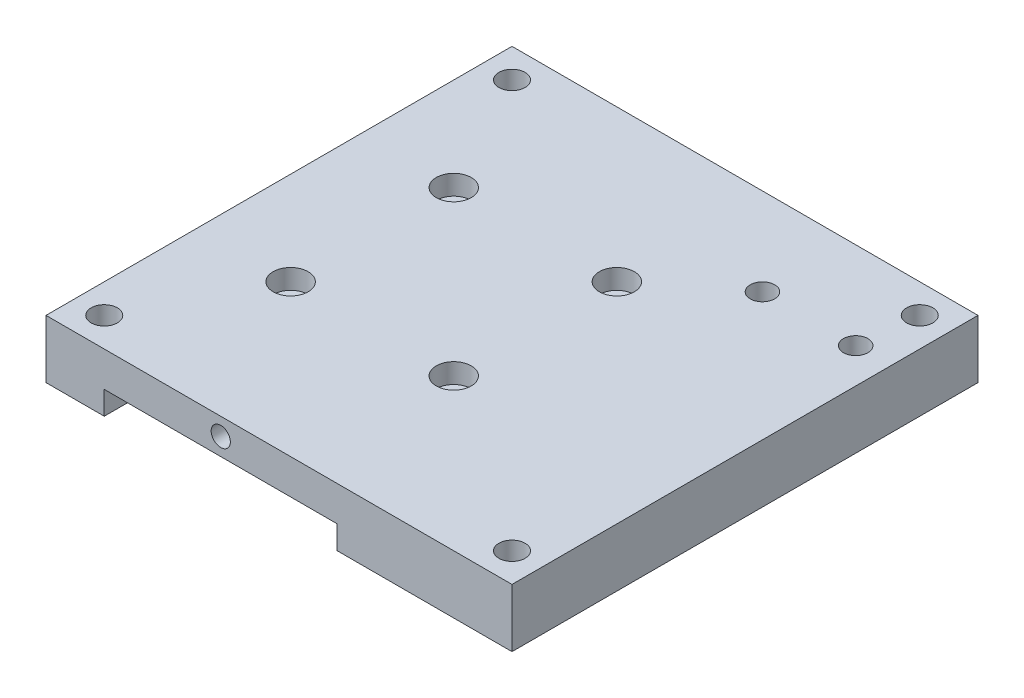
SolidWorks part; units mm, degrees
material "6061"
ref_plane "前视" through (0, 0, 0) normal (0, 0, 1) x (1, 0, 0)
ref_plane "上视" through (0, 0, 0) normal (0, 1, 0) x (1, 0, 0)
ref_plane "右视" through (0, 0, 0) normal (1, 0, 0) x (0, 0, -1)
sketch "草图1" plane through (0, 0, 0) normal (0, 1, 0) x (1, 0, 0)
  line L1 (-40, -40) -> (40, -40)
  line L2 (-40, -40) -> (-40, 40)
  line L3 (-40, 40) -> (40, 40)
  line L4 (40, -40) -> (40, 40)
  line L5 (-40, -40) -> (40, 40) construction
  line L6 (-40, 40) -> (40, -40) construction
  point P0 (0, 0)
  dimension "D1" = 80
  dimension "D2" = 80
extrude "凸台-拉伸1" add sketch "草图1" along normal blind 10
sketch "草图2" plane through (0, 0, 40) normal (0, 0, 1) x (1, 0, 0)
  line L0 (-40, 0) -> (40, 0) construction
  line L1 (-30, 0) -> (10, 0)
  line L2 (-30, 0) -> (-30, 4)
  line L3 (-30, 4) -> (10, 4)
  line L4 (10, 0) -> (10, 4)
  line L5 (-40, 10) -> (-40, 0) construction
  dimension "D1" = 40
  dimension "D2" = 10
  dimension "D3" = 4
extrude "切除-拉伸1" cut sketch "草图2" against normal through all
hole_wizard "打孔尺寸根据内六角圆柱头螺钉的类型1" positions "草图4" profile "草图3" counterbore size "M3" standard "Gb" end condition through all
sketch "草图4" plane through (0, 10, 0) normal (0, 1, 0) x (1, 0, 0)
  line L0 (-10, 40) -> (-10, 0) construction
  line L1 (-10, 0) -> (-30, 0) construction
  line L2 (-30, 40) -> (-30, -40) construction
  line L3 (10, 40) -> (-30, 40) construction
  point P0 (-24, 14)
  point P15 (4, 14)
  point P16 (4, -14)
  point P17 (-24, -14)
  dimension "D1" = 28
  dimension "D2" = 28
sketch "草图3" plane through (-24, 10, -14) normal (1, 0, 0) x (0, 0, 1)
  line L0 (0, 0) -> (0, 10)
  line L1 (0, 10) -> (1.7, 10)
  line L3 (1.7, 10) -> (1.7, 3.4)
  line L4 (1.7, 3.4) -> (3, 3.4)
  line L5 (3, 3.4) -> (3, 0)
  line L7 (3, 0) -> (0, 0)
  line L11 (0, -6.35) -> (0, 107.95) construction
  dimension "通孔孔直径" = 3.4
  dimension "通孔孔深度" = 10
  dimension "柱形沉头孔直径" = 6
  dimension "柱形沉头孔深度" = 3.4
hole_wizard "M5 螺纹孔1" positions "草图6" profile "草图5" tap size "M5" standard "Gb" end condition through all
sketch "草图6" plane through (0, 0, 0) normal (0, -1, 0) x (-1, 0, 0)
  line L0 (-40, -40) -> (-40, 40) construction
  point P0 (-18, 25)
  point P2 (-34, 25)
  point P7 (-40, 0)
  dimension "D1" = 16
  dimension "D2" = 6
  dimension "D3" = 25
sketch "草图5" plane through (18, 0, -25) normal (1, 0, 0) x (0, 0, -1)
  line L0 (0, 0) -> (0, 10)
  line L1 (0, 10) -> (2.1, 10)
  line L2 (2.1, 10) -> (2.1, 0)
  line L5 (2.1, 0) -> (0, 0)
  line L11 (0, -6.35) -> (0, 107.95) construction
  dimension "通孔螺纹孔钻头直径" = 4.2
  dimension "通孔螺纹孔钻头深度" = 10
cosmetic thread "孔螺蚊线1" parameters "D2"=5
cosmetic thread "孔螺蚊线2" parameters "D2"=5
hole_wizard "打孔尺寸根据内六角圆柱头螺钉的类型2" positions "草图8" profile "草图7" counterbore size "M4" standard "Gb" end condition through all
sketch "草图8" plane through (0, 0, 0) normal (0, -1, 0) x (-1, 0, 0)
  line L0 (-40, 0) -> (0, 0) construction
  line L1 (-40, -40) -> (-40, 40) construction
  line L2 (0, 0) -> (0, -40) construction
  line L4 (40, -40) -> (-40, -40) construction
  point P0 (35, -35)
  point P16 (-35, -35)
  point P17 (-35, 35)
  point P18 (35, 35)
  dimension "D1" = 70
  dimension "D2" = 70
sketch "草图7" plane through (-35, 0, 35) normal (1, 0, 0) x (0, 0, -1)
  line L0 (0, 0) -> (0, 10)
  line L1 (0, 10) -> (2.25, 10)
  line L3 (2.25, 10) -> (2.25, 5)
  line L4 (2.25, 5) -> (4, 5)
  line L5 (4, 5) -> (4, 0)
  line L7 (4, 0) -> (0, 0)
  line L11 (0, -6.35) -> (0, 107.95) construction
  dimension "通孔孔直径" = 4.5
  dimension "通孔孔深度" = 10
  dimension "柱形沉头孔直径" = 8
  dimension "柱形沉头孔深度" = 5
hole_wizard "M4 螺纹孔1" positions "草图10" profile "草图9" tap size "M4" standard "Gb"
sketch "草图10" plane through (0, 0, 40) normal (0, 0, 1) x (1, 0, 0)
  line L0 (-10, 4) -> (-10, 10) construction
  line L1 (10, 4) -> (-30, 4) construction
  line L2 (-40, 10) -> (40, 10) construction
  point P0 (-10, 7)
sketch "草图9" plane through (-10, 7, 40) normal (1, 0, 0) x (0, -1, 0)
  line L0 (0, 0) -> (0, 11.0914)
  line L1 (0, 11.0914) -> (1.65, 10.1)
  line L2 (1.65, 10.1) -> (1.65, 0)
  line L5 (1.65, 0) -> (0, 0)
  line L10 (0, 11.0914) -> (-1.65, 10.1) construction
  line L11 (0, -6.35) -> (0, 107.95) construction
  dimension "螺纹孔钻头直径" = 3.3
  dimension "螺纹孔钻头深度" = 10.1
  dimension "导头角度" = 118
cosmetic thread "孔螺蚊线3" parameters "D1"=8, "D2"=4
